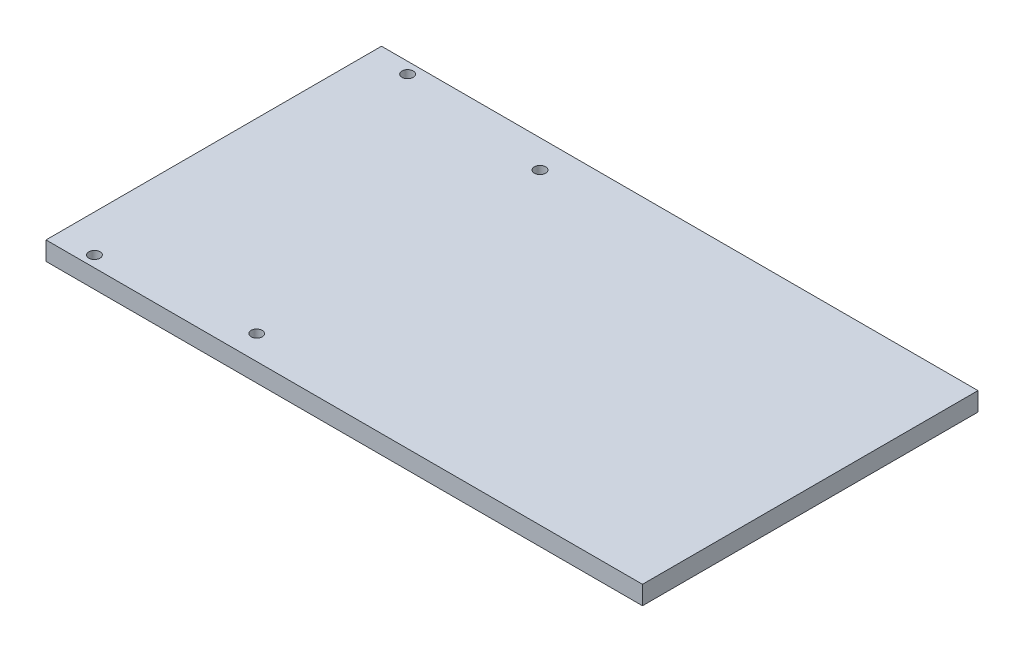
SolidWorks part; units mm, degrees
ref_plane "Front Plane" through (0, 0, 0) normal (0, 0, 1) x (1, 0, 0)
ref_plane "Top Plane" through (0, 0, 0) normal (0, 1, 0) x (1, 0, 0)
ref_plane "Right Plane" through (0, 0, 0) normal (1, 0, 0) x (0, 0, -1)
sketch "Sketch1" plane through (0, 0, 0) normal (0, 1, 0) x (1, 0, 0)
  line L1 (-96.0207, -6.3578) -> (103.9793, -6.3578)
  line L2 (-96.0207, -6.3578) -> (-96.0207, -96.3578)
  line L3 (-96.0207, -96.3578) -> (103.9793, -96.3578)
  line L4 (103.9793, -6.3578) -> (103.9793, -96.3578)
  circle A0 centre (-86.0207, -9.3578) radius 1.5
  circle A1 centre (-86.0207, -93.3578) radius 1.5
  circle A2 centre (93.9793, -9.3578) radius 1.5
  circle A3 centre (93.9793, -93.3578) radius 1.5
  dimension "D7" = 3
  dimension "D1" = 90
  dimension "D2" = 200
  dimension "D3" = 84
  dimension "D4" = 10
  dimension "D5" = 10
  dimension "D6" = 3
extrude "Boss-Extrude1" add sketch "Sketch1" along normal blind 5
sketch "Sketch2" plane through (0, 5, 0) normal (0, 1, 0) x (1, 0, 0)
  line L0 (-96.0207, -96.3578) -> (103.9793, -96.3578) construction
  line L1 (103.9793, -6.3578) -> (-36.0207, -6.3578)
  line L2 (103.9793, -6.3578) -> (103.9793, -96.3578)
  line L3 (103.9793, -96.3578) -> (-36.0207, -96.3578)
  line L4 (-36.0207, -6.3578) -> (-36.0207, -96.3578)
  dimension "D1" = 140
extrude "Cut-Extrude1" cut sketch "Sketch2" against normal through all
sketch "Sketch3" plane through (0, 5, 0) normal (0, 1, 0) x (1, 0, 0)
  circle A0 centre (-46.0067, -13.8578) radius 1.5
  circle A1 centre (-46.0067, -89.8578) radius 1.5
  dimension "D1" = 3
  dimension "D2" = 3
extrude "Cut-Extrude2" cut sketch "Sketch3" against normal through all
sketch "Sketch4" plane through (-36.0207, 0, 0) normal (1, 0, 0) x (0, 0, -1)
  line L4 (-6.3578, 5) -> (-96.3578, 5)
  line L5 (-96.3578, 5) -> (-96.3578, 0)
  line L6 (-96.3578, 0) -> (-6.3578, 0)
  line L7 (-6.3578, 0) -> (-6.3578, 5)
  line L8 (-6.3578, 5) -> (-96.3578, 5)
  line L9 (-96.3578, 5) -> (-96.3578, 0)
  line L10 (-96.3578, 0) -> (-6.3578, 0)
  line L11 (-6.3578, 0) -> (-6.3578, 5)
  dimension "D1" = 0
extrude "Boss-Extrude2" add sketch "Sketch4" along normal blind 100
